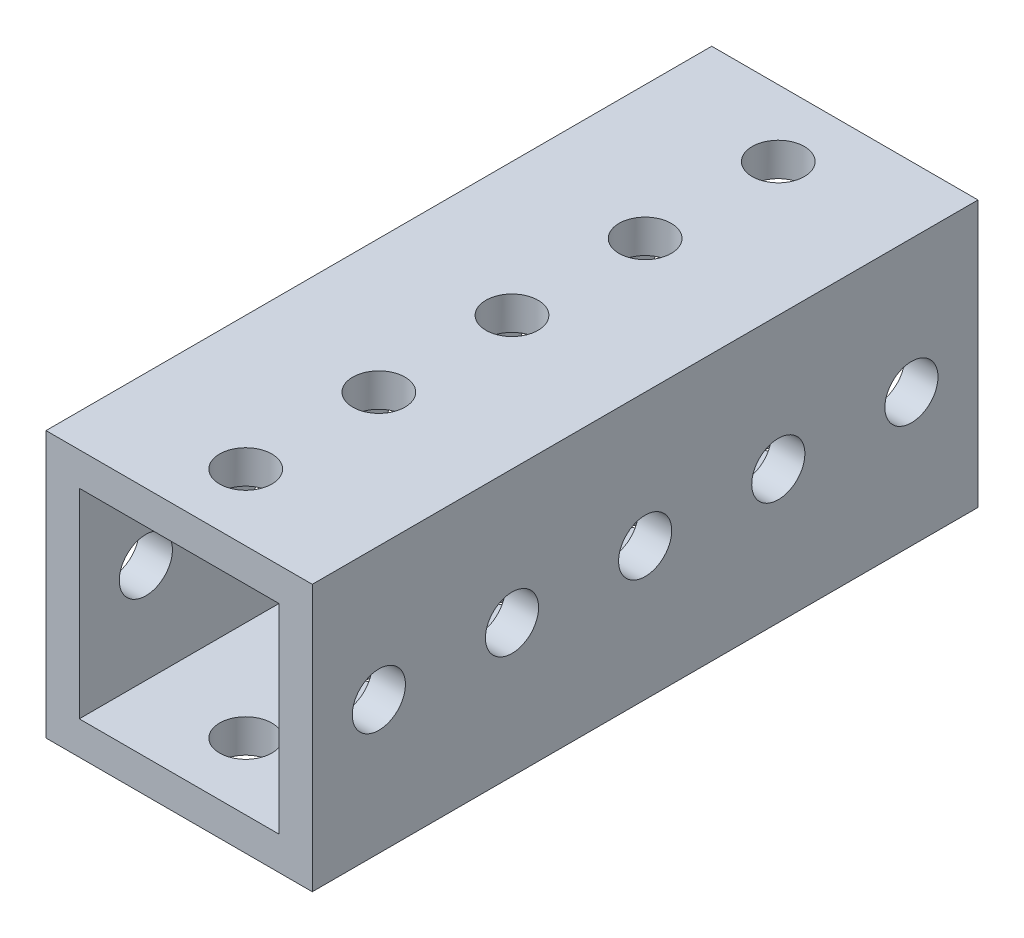
SolidWorks part; units mm, degrees
material "6061-T6 (SS)"
ref_plane "Front Plane" through (0, 0, 0) normal (0, 0, 1) x (1, 0, 0)
ref_plane "Top Plane" through (0, 0, 0) normal (0, 1, 0) x (1, 0, 0)
ref_plane "Right Plane" through (0, 0, 0) normal (1, 0, 0) x (0, 0, -1)
sketch "Sketch1" plane through (0, 0, 0) normal (0, 0, 1) x (1, 0, 0)
  line L1 (0, 0) -> (25.4, 0)
  line L2 (0, 0) -> (0, 25.4)
  line L3 (0, 25.4) -> (25.4, 25.4)
  line L4 (25.4, 0) -> (25.4, 25.4)
  dimension "D1" = 25.4
  dimension "D2" = 25.4
extrude "Boss-Extrude1" add sketch "Sketch1" along normal blind 63.5
shell "Shell1" thickness 3.175
sketch "Sketch2" plane through (0, 25.4, 0) normal (0, 1, 0) x (1, 0, 0)
  line L0 (25.4, 0) -> (0, 0) construction
  line L1 (0, -63.5) -> (0, 0) construction
  circle A0 centre (12.7, -6.35) radius 2.4892
  circle A1 centre (12.7, -19.05) radius 2.4892
  circle A2 centre (12.7, -31.75) radius 2.4892
  circle A3 centre (12.7, -44.45) radius 2.4892
  circle A4 centre (12.7, -57.15) radius 2.4892
  dimension "D1" = 4.9784
  dimension "D3" = 12.7
  dimension "D5" = 12.7
  dimension "D2" = 6.35
  dimension "D4" = 5
extrude "Cut-Extrude1" cut sketch "Sketch2" against normal blind 63.5
sketch "Sketch3" plane through (25.4, 0, 0) normal (1, 0, 0) x (0, 0, -1)
  line L0 (-63.5, 25.4) -> (0, 25.4) construction
  line L1 (-63.5, 0) -> (-63.5, 25.4) construction
  circle A0 centre (-57.15, 12.7) radius 2.5349
  circle A1 centre (-44.45, 12.7) radius 2.5349
  circle A2 centre (-31.75, 12.7) radius 2.5349
  circle A3 centre (-19.05, 12.7) radius 2.5349
  circle A4 centre (-6.35, 12.7) radius 2.5349
  dimension "D1" = 5.0698
  dimension "D5" = 12.7
  dimension "D2" = 12.7
  dimension "D3" = 6.35
  dimension "D4" = 5
extrude "Cut-Extrude2" cut sketch "Sketch3" against normal blind 63.5
